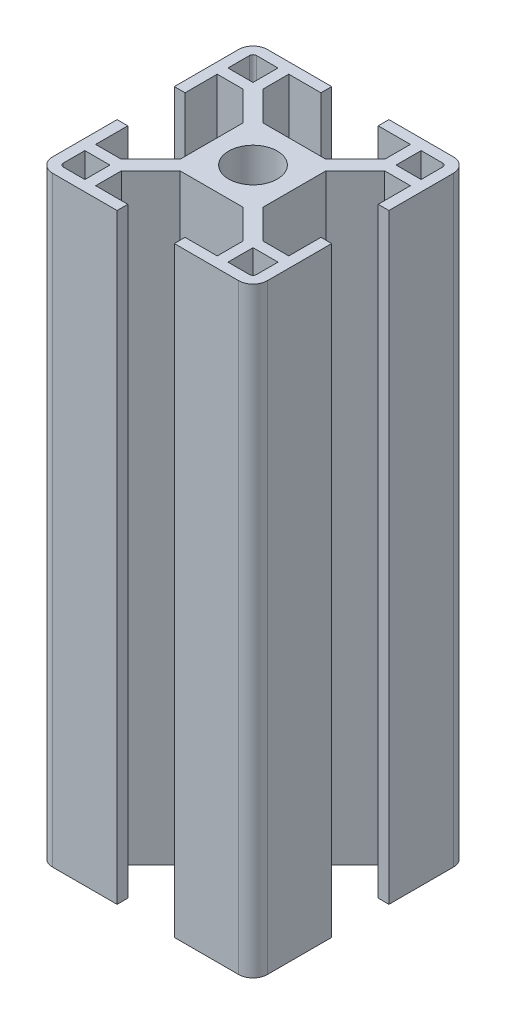
SolidWorks part; units mm, degrees
ref_plane "Płaszczyzna przednia" through (0, 0, 0) normal (0, 0, 1) x (1, 0, 0)
ref_plane "Płaszczyzna górna" through (0, 0, 0) normal (0, 1, 0) x (1, 0, 0)
ref_plane "Płaszczyzna prawa" through (0, 0, 0) normal (1, 0, 0) x (0, 0, -1)
sketch "Szkic2" plane through (0, 0, 0) normal (0, 1, 0) x (1, 0, 0)
  line L0 (10.0014, -10.0002) -> (13.5014, -10.0002)
  line L1 (10.0002, 10.0014) -> (13.5002, 10.0014)
  line L2 (10.0002, 10.0014) -> (10.0002, 13.5014)
  line L3 (10.0002, 13.5014) -> (13.0002, 13.5014)
  line L4 (13.5002, 10.0014) -> (13.5002, 13.0014)
  line L5 (10.0014, -10.0002) -> (10.0014, -13.5002)
  line L6 (10.0014, -13.5002) -> (13.0014, -13.5002)
  line L7 (13.5014, -10.0002) -> (13.5014, -13.0002)
  line L8 (-10.0002, -10.0014) -> (-10.0002, -13.5014)
  line L9 (-10.0002, -10.0014) -> (-13.5002, -10.0014)
  line L10 (-13.5002, -10.0014) -> (-13.5002, -13.0014)
  line L11 (-10.0002, -13.5014) -> (-13.0002, -13.5014)
  line L12 (-10.0014, 10.0002) -> (-13.5014, 10.0002)
  line L13 (-10.0014, 10.0002) -> (-10.0014, 13.5002)
  line L14 (-10.0014, 13.5002) -> (-13.0014, 13.5002)
  line L15 (-13.5014, 10.0002) -> (-13.5014, 13.0002)
  line L88 (15.0002, 4.0014) -> (15.0002, 13.0014)
  line L89 (13.0002, 15.0014) -> (4.0002, 15.0014)
  line L90 (4.0002, 15.0014) -> (4.0002, 13.5014)
  line L91 (4.0002, 13.5014) -> (8.5002, 13.5014)
  line L92 (8.5002, 13.5014) -> (8.5002, 9.9157)
  line L93 (8.5002, 9.9157) -> (4.386, 5.8014)
  line L94 (4.386, 5.8014) -> (-4.3856, 5.8014)
  line L95 (-4.3856, 5.8014) -> (-8.4998, 9.9157)
  line L96 (-8.4998, 9.9157) -> (-8.4998, 13.5014)
  line L97 (-8.4998, 13.5014) -> (-3.9998, 13.5014)
  line L98 (-3.9998, 13.5014) -> (-3.9998, 15.0014)
  line L99 (-3.9998, 15.0014) -> (-12.9998, 15.0014)
  line L100 (-14.9998, 13.0014) -> (-14.9998, 4.0014)
  line L101 (-14.9998, 4.0014) -> (-13.4998, 4.0014)
  line L102 (-13.4998, 4.0014) -> (-13.4998, 8.5014)
  line L103 (-13.4998, 8.5014) -> (-9.914, 8.5014)
  line L104 (-9.914, 8.5014) -> (-5.7998, 4.3872)
  line L105 (-5.7998, 4.3872) -> (-5.7998, -4.3843)
  line L106 (-5.7998, -4.3843) -> (-9.914, -8.4986)
  line L107 (-9.914, -8.4986) -> (-13.4998, -8.4986)
  line L108 (-13.4998, -8.4986) -> (-13.4998, -3.9986)
  line L109 (-13.4998, -3.9986) -> (-14.9998, -3.9986)
  line L110 (-14.9998, -3.9986) -> (-14.9998, -12.9986)
  line L111 (-12.9998, -14.9986) -> (-3.9998, -14.9986)
  line L112 (-3.9998, -14.9986) -> (-3.9998, -13.4986)
  line L113 (-3.9998, -13.4986) -> (-8.4998, -13.4986)
  line L114 (-8.4998, -13.4986) -> (-8.4998, -9.9128)
  line L115 (-8.4998, -9.9128) -> (-4.3856, -5.7986)
  line L116 (-4.3856, -5.7986) -> (4.386, -5.7986)
  line L117 (4.386, -5.7986) -> (8.5002, -9.9128)
  line L118 (8.5002, -9.9128) -> (8.5002, -13.4986)
  line L119 (8.5002, -13.4986) -> (4.0002, -13.4986)
  line L120 (4.0002, -13.4986) -> (4.0002, -14.9986)
  line L121 (4.0002, -14.9986) -> (13.0002, -14.9986)
  line L122 (15.0002, -12.9986) -> (15.0002, -3.9986)
  line L123 (15.0002, -3.9986) -> (13.5002, -3.9986)
  line L124 (13.5002, -3.9986) -> (13.5002, -8.4986)
  line L125 (13.5002, -8.4986) -> (9.9144, -8.4986)
  line L126 (9.9144, -8.4986) -> (5.8002, -4.3843)
  line L127 (5.8002, -4.3843) -> (5.8002, 4.3872)
  line L128 (5.8002, 4.3872) -> (9.9144, 8.5014)
  line L129 (9.9144, 8.5014) -> (13.5002, 8.5014)
  line L130 (13.5002, 8.5014) -> (13.5002, 4.0014)
  line L131 (13.5002, 4.0014) -> (15.0002, 4.0014)
  circle A0 centre (0, 0) radius 3.4
  arc A1 (13.0002, 13.5014) -> (13.5002, 13.0014) centre (13.0002, 13.0014) cw
  arc A2 (13.5014, -13.0002) -> (13.0014, -13.5002) centre (13.0014, -13.0002) cw
  arc A3 (-13.0002, -13.5014) -> (-13.5002, -13.0014) centre (-13.0002, -13.0014) cw
  arc A4 (-13.5014, 13.0002) -> (-13.0014, 13.5002) centre (-13.0014, 13.0002) cw
  arc A8 (15.0002, 13.0014) -> (13.0002, 15.0014) centre (13.0002, 13.0014) ccw
  arc A9 (-12.9998, 15.0014) -> (-14.9998, 13.0014) centre (-12.9998, 13.0014) ccw
  arc A10 (-14.9998, -12.9986) -> (-12.9998, -14.9986) centre (-12.9998, -12.9986) ccw
  arc A11 (13.0002, -14.9986) -> (15.0002, -12.9986) centre (13.0002, -12.9986) ccw
  point P82 (0, 0)
  dimension "D2" = 6.8
  dimension "D5" = 0.5
  dimension "D1" = 30
  dimension "D3" = 3.5
  dimension "D4" = 3.5
  dimension "D6" = 1.5
  dimension "D7" = 1.5
  dimension "D8" = 4
extrude "Dodanie-wyciągnięcie1" add sketch "Szkic2" along normal blind 84
equation "\"D4@Szkic2\"=\"D3@Szkic2\""
equation "\"D7@Szkic2\"=\"D6@Szkic2\""
